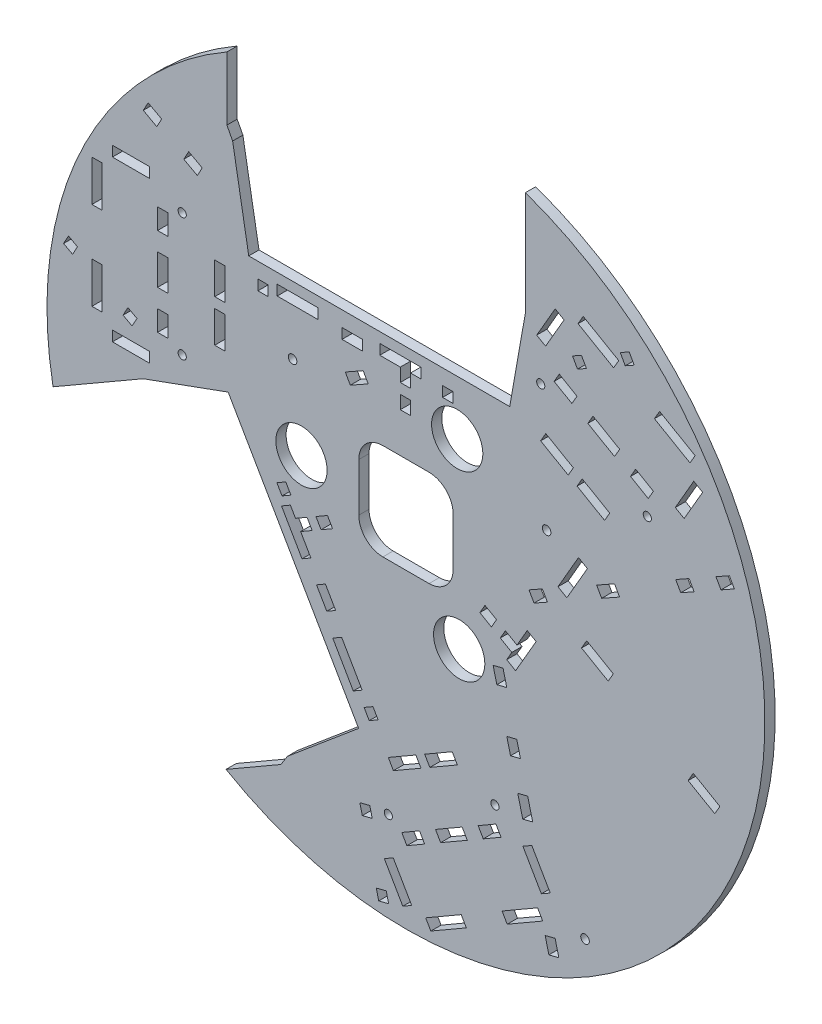
SolidWorks part; units mm, degrees
material "Balsa"
ref_plane "Plan de face" through (0, 0, 0) normal (0, 0, 1) x (1, 0, 0)
ref_plane "Plan de dessus" through (0, 0, 0) normal (0, 1, 0) x (1, 0, 0)
ref_plane "Plan de droite" through (0, 0, 0) normal (1, 0, 0) x (0, 0, -1)
sketch "Esquisse1" plane through (0, 0, 0) normal (0, 0, 1) x (1, 0, 0)
  circle A0 centre (148.0804, -12.1102) radius 175
  dimension "D1" = 350
extrude "Boss.-Extru.1" add sketch "Esquisse1" along normal blind 5
sketch "Esquisse2" plane through (0, 0, 5) normal (0, 0, 1) x (1, 0, 0)
  line L0 (135.3118, 53.7774) -> (135.3118, 48.7774)
  line L1 (5, 72.2774) -> (23, 72.2774)
  line L2 (5, 72.2774) -> (5, 67.2774)
  line L3 (5, 67.2774) -> (23, 67.2774)
  line L4 (23, 72.2774) -> (23, 67.2774)
  line L5 (-5, 62.2774) -> (0, 62.2774)
  line L6 (-5, 62.2774) -> (-5, 42.2774)
  line L7 (-5, 42.2774) -> (0, 42.2774)
  line L8 (0, 62.2774) -> (0, 42.2774)
  line L9 (-5, 19.2774) -> (0, 19.2774)
  line L10 (-5, 19.2774) -> (-5, -0.7226)
  line L11 (-5, -0.7226) -> (0, -0.7226)
  line L12 (0, 19.2774) -> (0, -0.7226)
  line L13 (5, -5.7226) -> (23, -5.7226)
  line L14 (5, -5.7226) -> (5, -10.7226)
  line L15 (5, -10.7226) -> (23, -10.7226)
  line L16 (23, -5.7226) -> (23, -10.7226)
  line L17 (27, 14.2774) -> (32, 14.2774)
  line L18 (27, 14.2774) -> (27, 4.2774)
  line L19 (27, 4.2774) -> (32, 4.2774)
  line L20 (32, 14.2774) -> (32, 4.2774)
  line L21 (27, 38.2774) -> (32, 38.2774)
  line L22 (27, 38.2774) -> (27, 23.2774)
  line L23 (27, 23.2774) -> (32, 23.2774)
  line L24 (32, 38.2774) -> (32, 23.2774)
  line L25 (27, 57.2774) -> (32, 57.2774)
  line L26 (27, 57.2774) -> (27, 47.2774)
  line L27 (27, 47.2774) -> (32, 47.2774)
  line L28 (32, 57.2774) -> (32, 47.2774)
  line L29 (54.86, 48.7774) -> (59.86, 48.7774)
  line L30 (54.86, 48.7774) -> (54.86, 33.2774)
  line L31 (54.86, 33.2774) -> (59.86, 33.2774)
  line L32 (59.86, 48.7774) -> (59.86, 33.2774)
  line L33 (54.86, 28.2774) -> (59.86, 28.2774)
  line L34 (54.86, 28.2774) -> (54.86, 12.7774)
  line L35 (54.86, 12.7774) -> (59.86, 12.7774)
  line L36 (59.86, 28.2774) -> (59.86, 12.7774)
  line L37 (85.3118, 53.7774) -> (105.3118, 53.7774)
  line L38 (85.3118, 53.7774) -> (85.3118, 48.7774)
  line L39 (85.3118, 48.7774) -> (105.3118, 48.7774)
  line L40 (105.3118, 53.7774) -> (105.3118, 48.7774)
  line L41 (145.3118, 37.2774) -> (150.3118, 37.2774)
  line L42 (145.3118, 37.2774) -> (145.3118, 30.7774)
  line L43 (145.3118, 30.7774) -> (150.3118, 30.7774)
  line L44 (150.3118, 37.2774) -> (150.3118, 30.7774)
  line L45 (135.3118, 48.7774) -> (145.3118, 48.7774)
  line L46 (155.3118, 48.7774) -> (135.3118, 48.7774) construction
  line L47 (145.3118, 48.7774) -> (145.3118, 42.2774)
  line L48 (145.3118, 42.2774) -> (150.3118, 42.2774)
  line L49 (150.3118, 42.2774) -> (150.3118, 48.7774)
  line L50 (150.3118, 48.7774) -> (155.3118, 48.7774)
  line L51 (155.3118, 48.7774) -> (155.3118, 53.7774)
  line L52 (155.3118, 53.7774) -> (135.3118, 53.7774)
  line L53 (292.7025, 69.6073) -> (283.7025, 54.0188)
  line L54 (292.7025, 69.6073) -> (288.3723, 72.1073)
  line L55 (288.3723, 72.1073) -> (279.3723, 56.5188)
  line L56 (283.7025, 54.0188) -> (279.3723, 56.5188)
  line L57 (289.0422, 83.2676) -> (286.5422, 78.9374)
  line L58 (289.0422, 83.2676) -> (271.7217, 93.2676)
  line L59 (271.7217, 93.2676) -> (269.2217, 88.9374)
  line L60 (286.5422, 78.9374) -> (269.2217, 88.9374)
  line L61 (251.8031, 104.7676) -> (249.3031, 100.4374)
  line L62 (251.8031, 104.7676) -> (234.4826, 114.7676)
  line L63 (234.4826, 114.7676) -> (231.9826, 110.4374)
  line L64 (249.3031, 100.4374) -> (231.9826, 110.4374)
  line L65 (225.1525, 108.6073) -> (216.1525, 93.0188)
  line L66 (225.1525, 108.6073) -> (220.8223, 111.1073)
  line L67 (220.8223, 111.1073) -> (211.8223, 95.5188)
  line L68 (216.1525, 93.0188) -> (211.8223, 95.5188)
  line L69 (231.473, 79.5547) -> (228.973, 75.2246)
  line L70 (231.473, 79.5547) -> (222.8127, 84.5547)
  line L71 (222.8127, 84.5547) -> (220.3127, 80.2246)
  line L72 (228.973, 75.2246) -> (220.3127, 80.2246)
  line L73 (252.2576, 67.5547) -> (249.7576, 63.2246)
  line L74 (252.2576, 67.5547) -> (239.2672, 75.0547)
  line L75 (239.2672, 75.0547) -> (236.7672, 70.7246)
  line L76 (249.7576, 63.2246) -> (236.7672, 70.7246)
  line L77 (268.7121, 58.0547) -> (266.2121, 53.7246)
  line L78 (268.7121, 58.0547) -> (260.0518, 63.0547)
  line L79 (260.0518, 63.0547) -> (257.5518, 58.7246)
  line L80 (266.2121, 53.7246) -> (257.5518, 58.7246)
  line L81 (247.4209, 38.1773) -> (244.9209, 33.8472)
  line L82 (247.4209, 38.1773) -> (233.9975, 45.9273)
  line L83 (233.9975, 45.9273) -> (231.4975, 41.5972)
  line L84 (244.9209, 33.8472) -> (231.4975, 41.5972)
  line L85 (229.6673, 48.4273) -> (227.1673, 44.0972)
  line L86 (229.6673, 48.4273) -> (216.2439, 56.1773)
  line L87 (216.2439, 56.1773) -> (213.7439, 51.8472)
  line L88 (227.1673, 44.0972) -> (213.7439, 51.8472)
  line L89 (211.5251, -33.996) -> (207.195, -31.496)
  line L90 (236.5251, 9.3053) -> (226.5251, -8.0153)
  line L91 (236.5251, 9.3053) -> (232.195, 11.8053)
  line L92 (232.195, 11.8053) -> (222.195, -5.5153)
  line L93 (226.5251, -8.0153) -> (222.195, -5.5153)
  line L94 (192.2357, -34.4063) -> (189.7357, -38.7364)
  line L95 (192.2357, -34.4063) -> (186.6065, -31.1563)
  line L96 (186.6065, -31.1563) -> (184.1065, -35.4864)
  line L97 (189.7357, -38.7364) -> (184.1065, -35.4864)
  line L98 (207.195, -31.496) -> (202.195, -40.1563)
  line L99 (202.195, -40.1563) -> (196.5658, -36.9063)
  line L100 (196.5658, -36.9063) -> (194.0658, -41.2364)
  line L101 (194.0658, -41.2364) -> (199.695, -44.4864)
  line L102 (199.695, -44.4864) -> (197.195, -48.8165)
  line L103 (197.195, -48.8165) -> (201.5251, -51.3165)
  line L104 (201.5251, -51.3165) -> (211.5251, -33.996)
  line L105 (146.5388, -178.2153) -> (137.5388, -162.6268)
  line L106 (146.5388, -178.2153) -> (150.869, -175.7153)
  line L107 (150.869, -175.7153) -> (141.869, -160.1268)
  line L108 (137.5388, -162.6268) -> (141.869, -160.1268)
  line L109 (160.1991, -181.8755) -> (157.6991, -177.5454)
  line L110 (160.1991, -181.8755) -> (177.5196, -171.8755)
  line L111 (177.5196, -171.8755) -> (175.0196, -167.5454)
  line L112 (157.6991, -177.5454) -> (175.0196, -167.5454)
  line L113 (197.4382, -160.3755) -> (194.9382, -156.0454)
  line L114 (197.4382, -160.3755) -> (214.7587, -150.3755)
  line L115 (214.7587, -150.3755) -> (212.2587, -146.0454)
  line L116 (194.9382, -156.0454) -> (212.2587, -146.0454)
  line L117 (214.0888, -139.2153) -> (205.0888, -123.6268)
  line L118 (214.0888, -139.2153) -> (218.4189, -136.7153)
  line L119 (218.4189, -136.7153) -> (209.4189, -121.1268)
  line L120 (205.0888, -123.6268) -> (209.4189, -121.1268)
  line L121 (185.7683, -130.1627) -> (183.2683, -125.8326)
  line L122 (185.7683, -130.1627) -> (194.4286, -125.1627)
  line L123 (194.4286, -125.1627) -> (191.9286, -120.8326)
  line L124 (183.2683, -125.8326) -> (191.9286, -120.8326)
  line L125 (164.9837, -142.1627) -> (162.4837, -137.8326)
  line L126 (164.9837, -142.1627) -> (177.9741, -134.6627)
  line L127 (177.9741, -134.6627) -> (175.4741, -130.3326)
  line L128 (162.4837, -137.8326) -> (175.4741, -130.3326)
  line L129 (148.5292, -151.6627) -> (146.0292, -147.3326)
  line L130 (148.5292, -151.6627) -> (157.1895, -146.6627)
  line L131 (157.1895, -146.6627) -> (154.6895, -142.3326)
  line L132 (146.0292, -147.3326) -> (154.6895, -142.3326)
  line L133 (141.9604, -123.2852) -> (139.4604, -118.9551)
  line L134 (141.9604, -123.2852) -> (155.3838, -115.5352)
  line L135 (155.3838, -115.5352) -> (152.8838, -111.2051)
  line L136 (139.4604, -118.9551) -> (152.8838, -111.2051)
  line L137 (159.7139, -113.0352) -> (157.2139, -108.7051)
  line L138 (159.7139, -113.0352) -> (173.1373, -105.2852)
  line L139 (173.1373, -105.2852) -> (170.6373, -100.9551)
  line L140 (157.2139, -108.7051) -> (170.6373, -100.9551)
  line L141 (97.4044, -56.1119) -> (101.7345, -53.6119)
  line L142 (122.4044, -99.4132) -> (112.4044, -82.0927)
  line L143 (122.4044, -99.4132) -> (126.7345, -96.9132)
  line L144 (126.7345, -96.9132) -> (116.7345, -79.5927)
  line L145 (112.4044, -82.0927) -> (116.7345, -79.5927)
  line L146 (106.6938, -39.2017) -> (104.1938, -34.8716)
  line L147 (106.6938, -39.2017) -> (112.323, -35.9517)
  line L148 (112.323, -35.9517) -> (109.823, -31.6216)
  line L149 (104.1938, -34.8716) -> (109.823, -31.6216)
  line L150 (101.7345, -53.6119) -> (96.7345, -44.9517)
  line L151 (96.7345, -44.9517) -> (102.3637, -41.7017)
  line L152 (102.3637, -41.7017) -> (99.8637, -37.3716)
  line L153 (99.8637, -37.3716) -> (94.2345, -40.6216)
  line L154 (94.2345, -40.6216) -> (91.7345, -36.2914)
  line L155 (91.7345, -36.2914) -> (87.4044, -38.7914)
  line L156 (87.4044, -38.7914) -> (97.4044, -56.1119)
  line L157 (135.3118, 53.7774) -> (135.3118, 48.7774) construction
  line L158 (105.3118, 53.7774) -> (135.3118, 53.7774) construction
  point P83 (148.0804, -12.1102)
  point P192 (148.0804, -12.1102)
  point P193 (148.0804, -12.1102)
  dimension "D1" = 3
extrude "Enlèv. mat.-Extru.1" cut sketch "Esquisse2" against normal blind 5
sketch "Esquisse6" plane through (0, 0, 5) normal (0, 0, 1) x (1, 0, 0)
  line L0 (93.9998, -7.2151) -> (100.2998, -18.127) construction
  line L1 (206.3213, 102.2219) -> (206.3213, 185.5637)
  line L2 (125.0804, -35.6102) -> (171.0804, -35.6102) construction
  line L3 (125.0804, -35.6102) -> (125.0804, 11.3898) construction
  line L4 (125.0804, 11.3898) -> (171.0804, 11.3898) construction
  line L5 (171.0804, -35.6102) -> (171.0804, 11.3898) construction
  line L6 (125.0804, -35.6102) -> (171.0804, 11.3898) construction
  line L7 (125.0804, 11.3898) -> (171.0804, -35.6102) construction
  line L8 (206.3213, 185.5637) -> (60.7972, 185.5637)
  line L9 (71.4438, 58.7774) -> (63.5848, 103.3483)
  line L10 (71.4438, 58.7774) -> (198.6608, 58.7774)
  line L11 (198.6608, 58.7774) -> (206.3213, 102.2219)
  line L12 (60.7972, 185.5637) -> (60.7972, 108.6824)
  line L13 (19.9456, -18.8381) -> (-52.2306, -60.5091)
  line L14 (-52.2306, -60.5091) -> (20.5314, -186.5366)
  line L15 (63.5848, 103.3483) -> (60.7972, 108.6824)
  line L16 (125.0083, -113.9232) -> (90.3383, -143.0148)
  line L17 (125.0083, -113.9232) -> (61.3998, -3.7501)
  line L18 (61.3998, -3.7501) -> (19.9456, -18.8381)
  line L19 (136.8304, -23.8602) -> (159.3304, -23.8602) construction
  line L20 (236.1714, -21.3074) -> (249.1617, -28.8074)
  line L21 (236.1714, -21.3074) -> (233.6714, -25.6375)
  line L22 (249.1617, -28.8074) -> (246.6617, -33.1375)
  line L23 (233.6714, -25.6375) -> (246.6617, -33.1375)
  line L24 (288.1329, -51.3074) -> (301.1233, -58.8074)
  line L25 (288.1329, -51.3074) -> (285.6329, -55.6375)
  line L26 (301.1233, -58.8074) -> (298.6233, -63.1375)
  line L27 (285.6329, -55.6375) -> (298.6233, -63.1375)
  line L28 (226.5251, -8.0153) -> (236.5251, 9.3053) construction
  line L29 (279.3723, 56.5188) -> (283.7025, 54.0188) construction
  line L30 (136.8304, -0.3602) -> (159.3304, -0.3602) construction
  line L31 (64.5427, 103.6743) -> (63.0102, 106.6067) construction
  line L32 (20.5314, -186.5366) -> (87.1126, -148.0959)
  line L33 (90.3383, -143.0148) -> (87.1126, -148.0959)
  line L34 (125.0804, -23.8602) -> (125.0804, -0.3602)
  line L35 (136.8304, -35.6102) -> (159.3304, -35.6102)
  line L36 (159.3304, -35.6102) -> (159.6478, -35.9264)
  line L37 (171.0804, -23.8602) -> (171.0804, -0.3602)
  line L38 (159.3304, 11.3898) -> (136.8304, 11.3898)
  circle A0 centre (173.06, 32.2774) radius 12.5
  circle A1 centre (174.0314, -55.9369) radius 12.5
  circle A2 centre (97.1498, -12.671) radius 12.5
  arc A3 (125.0804, -23.8602) -> (136.8304, -35.6102) centre (136.8304, -23.8602) ccw
  arc A4 (171.0804, -23.8602) -> (159.3304, -35.6102) centre (159.3304, -23.8602) cw
  arc A5 (171.0804, -0.3602) -> (159.3304, 11.3898) centre (159.3304, -0.3602) ccw
  arc A6 (125.0804, -0.3602) -> (136.8304, 11.3898) centre (136.8304, -0.3602) cw
  point P2 (148.0804, -12.1102)
  point P8 (148.0804, -12.1102)
  point P10 (148.0804, -12.1102)
  point P35 (148.0804, -12.1102)
  point P48 (148.0804, -12.1102)
  dimension "D12" = 25
  dimension "D23" = 11.75
  dimension "D3" = 47
  dimension "D4" = 46
  dimension "D5" = 70.8876
  dimension "D6" = 50.5804
  dimension "D7" = 127.217
  dimension "D8" = 100
  dimension "D9" = 100
  dimension "D10" = 145.5241
  dimension "D11" = 43.4444
  dimension "D13" = 5
  dimension "D14" = 15
  dimension "D15" = 15
  dimension "D16" = 45
  dimension "D17" = 15
  dimension "D18" = 89
  dimension "D19" = 2
  dimension "D20" = 1
  dimension "D21" = 11.75
  dimension "D22" = 11.75
  dimension "D1" = 3
extrude "Enlèv. mat.-Extru.6" cut sketch "Esquisse6" against normal blind 5 contours L33 L16 L17 L18 L13 L14 L32 | A2 | L15 L9 L10 L11 L1 L8 L12 | A6 L34 A3 L35 A4 L37 A5 L38 | A1 | A0 | L25 L27 L26 L24 | L21 L23 L22 L20
hole_wizard "Trous de centrage Ø4.0mm1" positions "Esquisse7" profile "Esquisse8" hole size "Ø4.0" standard "Ansi Metric" end condition through all
sketch "Esquisse7" plane through (148.0804, -12.1102, -78) normal (0, 0, -1) x (1, 0, 0)
  point P0 (65.7012, -88.0226)
  point P3 (117.6627, -58.0226)
  point P6 (-109.0804, -72.8876)
  point P9 (-109.0804, -12.8876)
  point P12 (-8.5823, 130.9102)
  point P15 (43.3792, 100.9102)
sketch "Esquisse8" plane through (213.7816, 75.9124, -78) normal (1, 0, 0) x (0, 1, 0)
  line L0 (0, 0) -> (0, 83)
  line L1 (0, 83) -> (2, 83)
  line L2 (2, 83) -> (2, 0)
  line L3 (2, 0) -> (0, 0)
  line L4 (0, -6.35) -> (0, 107.95) construction
  dimension "Diamètre du perçage jusqu'au prochain" = 4
  dimension "Profondeur du perçage jusqu'au prochain" = 83
sketch "Esquisse9" plane through (0, 0, 5) normal (0, 0, 1) x (1, 0, 0)
  line L0 (301.6473, 32.8747) -> (299.2005, 37.2351)
  line L1 (301.6473, 32.8747) -> (308.1879, 36.5449)
  line L2 (299.2005, 37.2351) -> (305.7411, 40.9053)
  line L3 (308.1879, 36.5449) -> (305.7411, 40.9053)
  line L4 (282.0254, 21.8642) -> (279.5786, 26.2246)
  line L5 (282.0254, 21.8642) -> (288.566, 25.5344)
  line L6 (279.5786, 26.2246) -> (286.1192, 29.8948)
  line L7 (288.566, 25.5344) -> (286.1192, 29.8948)
  line L8 (252.2089, 5.133) -> (249.7621, 9.4935)
  line L9 (252.2089, 5.133) -> (243.488, 0.2395)
  line L10 (249.7621, 9.4935) -> (241.0412, 4.5999)
  line L11 (243.488, 0.2395) -> (241.0412, 4.5999)
  line L12 (214.6084, -10.2326) -> (217.0552, -14.593)
  line L13 (214.6084, -10.2326) -> (208.0678, -13.9027)
  line L14 (217.0552, -14.593) -> (210.5146, -18.2632)
  line L15 (208.0678, -13.9027) -> (210.5146, -18.2632)
  line L16 (217.0552, -14.593) -> (243.488, 0.2395) construction
  line L17 (214.6084, -10.2326) -> (217.0552, -14.593) construction
  line L18 (259.3473, 106.6065) -> (254.9869, 104.1597)
  line L19 (259.3473, 106.6065) -> (256.9005, 110.9669)
  line L20 (254.9869, 104.1597) -> (252.5401, 108.5201)
  line L21 (256.9005, 110.9669) -> (252.5401, 108.5201)
  line L22 (236.0696, 93.5445) -> (231.7091, 91.0977)
  line L23 (236.0696, 93.5445) -> (233.6228, 97.9049)
  line L24 (231.7091, 91.0977) -> (229.2624, 95.4581)
  line L25 (233.6228, 97.9049) -> (229.2624, 95.4581)
  line L26 (129.6754, 33.8428) -> (120.9546, 28.9492)
  line L27 (129.6754, 33.8428) -> (127.2286, 38.2032)
  line L28 (120.9546, 28.9492) -> (118.5078, 33.3096)
  line L29 (127.2286, 38.2032) -> (118.5078, 33.3096)
  line L30 (259.3473, 106.6065) -> (120.9546, 28.9492) construction
  line L31 (301.6473, 32.8747) -> (217.0552, -14.593) construction
  line L32 (-16.4384, 23.2791) -> (-12.0459, 20.8904)
  line L33 (-16.4384, 23.2791) -> (-18.8272, 18.8866)
  line L34 (-12.0459, 20.8904) -> (-14.4347, 16.4979)
  line L35 (-18.8272, 18.8866) -> (-14.4347, 16.4979)
  line L36 (12.552, 7.5136) -> (16.9445, 5.1249)
  line L37 (12.552, 7.5136) -> (10.1633, 3.1211)
  line L38 (16.9445, 5.1249) -> (14.5558, 0.7324)
  line L39 (10.1633, 3.1211) -> (14.5558, 0.7324)
  line L42 (-26.9196, -12.1102) -> (148.0804, -12.1102) construction
  line L44 (22.4127, 98.9071) -> (29.0015, 95.324)
  line L45 (22.4127, 98.9071) -> (20.024, 94.5146)
  line L46 (29.0015, 95.324) -> (26.6128, 90.9315)
  line L47 (20.024, 94.5146) -> (26.6128, 90.9315)
  line L48 (42.179, 88.1579) -> (48.7677, 84.5748)
  line L49 (42.179, 88.1579) -> (39.7903, 83.7654)
  line L50 (48.7677, 84.5748) -> (46.379, 80.1823)
  line L51 (39.7903, 83.7654) -> (46.379, 80.1823)
  line L53 (148.0804, -12.1102) -> (9.6568, -109.2191) construction
  line L55 (129.7636, 187.6323) -> (148.0804, -12.1102) construction
  circle A0 centre (148.0804, -12.1102) radius 175 construction
  line B0 (154.106, -73.5915) -> (185.6214, -199.5155) construction
  line B1 (126.7996, -149.8343) -> (125.5857, -144.9839)
  line B2 (130.4361, -143.77) -> (125.5857, -144.9839)
  line B3 (131.65, -148.6204) -> (126.7996, -149.8343)
  line B4 (131.65, -148.6204) -> (130.4361, -143.77)
  line B5 (134.8115, -181.8469) -> (133.5976, -176.9965)
  line B6 (138.448, -175.7826) -> (133.5976, -176.9965)
  line B7 (139.6619, -180.633) -> (134.8115, -181.8469)
  line B8 (139.6619, -180.633) -> (138.448, -175.7826)
  line B9 (190.562, -54.5014) -> (195.4124, -53.2875)
  line B10 (197.2333, -60.5631) -> (195.4124, -53.2875)
  line B11 (192.3829, -61.777) -> (190.562, -54.5014)
  line B12 (192.3829, -61.777) -> (197.2333, -60.5631)
  line B13 (202.089, -79.9647) -> (197.2386, -81.1786)
  line B14 (199.0595, -88.4542) -> (197.2386, -81.1786)
  line B15 (203.9099, -87.2403) -> (202.089, -79.9647)
  line B16 (203.9099, -87.2403) -> (199.0595, -88.4542)
  line B17 (222.6043, -161.9364) -> (217.7539, -163.1503)
  line B18 (215.933, -155.8747) -> (217.7539, -163.1503)
  line B19 (220.7834, -154.6608) -> (222.6043, -161.9364)
  line B20 (220.7834, -154.6608) -> (215.933, -155.8747)
  dimension "D9" = 170.2546
  dimension "D1" = 10
  dimension "D2" = 5
  dimension "D3" = 7.5
  dimension "D4" = 10
  dimension "D5" = 7.5
  dimension "D6" = 7.5
  dimension "D7" = 5
  dimension "D8" = 117
  dimension "D10" = 167.3371
  dimension "D11" = 69
  dimension "D12" = 35.051
  dimension "D13" = 30.31
  dimension "D14" = 5
sketch_block_instance "Bloc1-1"
sketch_block "Bloc1"
extrude "Holes catchers of glass" cut sketch "Esquisse9" against normal blind 10
sketch "Esquisse10" plane through (0, 0, 5) normal (0, 0, 1) x (1, 0, 0)
  line L0 (89.4961, -27.6144) -> (91.9961, -31.9445)
  line L1 (89.4961, -27.6144) -> (85.1672, -30.1137)
  line L2 (91.9961, -31.9445) -> (87.6672, -34.4438)
  line L3 (85.1672, -30.1137) -> (87.6672, -34.4438)
  dimension "D1" = 4.9986
extrude "Holes boards servo" cut sketch "Esquisse10" against normal blind 10
sketch "Esquisse11" plane through (0, 0, 5) normal (0, 0, 1) x (1, 0, 0)
  line L0 (109.4829, -72.2325) -> (104.4829, -63.5722)
  line L1 (109.4829, -72.2325) -> (113.813, -69.7325)
  line L2 (104.4829, -63.5722) -> (108.813, -61.0722)
  line L3 (113.813, -69.7325) -> (108.813, -61.0722)
  line L4 (125.166, -99.3964) -> (108.8992, -71.2215) construction
  line L6 (116.7345, -79.5927) -> (112.4044, -82.0927) construction
  line L7 (130.166, -108.0567) -> (134.4961, -105.5567)
  line L8 (130.166, -108.0567) -> (127.666, -103.7266)
  line L9 (134.4961, -105.5567) -> (131.9961, -101.2266)
  line L10 (127.666, -103.7266) -> (131.9961, -101.2266)
  line L11 (207.4302, -101.3064) -> (209.8581, -111.0072)
  line L12 (170.9253, 51.2774) -> (165.9253, 51.2774)
  line L13 (170.9253, 51.2774) -> (170.9253, 46.2774)
  line L14 (170.9253, 46.2774) -> (165.9253, 46.2774)
  line L15 (165.9253, 51.2774) -> (165.9253, 46.2774)
  line L16 (126.9253, 51.2774) -> (116.9253, 51.2774)
  line L17 (126.9253, 51.2774) -> (126.9253, 46.2774)
  line L18 (126.9253, 46.2774) -> (116.9253, 46.2774)
  line L19 (116.9253, 51.2774) -> (116.9253, 46.2774)
  line L20 (80.9253, 51.2774) -> (75.9253, 51.2774)
  line L21 (80.9253, 51.2774) -> (80.9253, 46.2774)
  line L22 (80.9253, 46.2774) -> (75.9253, 46.2774)
  line L23 (75.9253, 51.2774) -> (75.9253, 46.2774)
  line L24 (207.4302, -101.3064) -> (202.5798, -102.5203)
  line L25 (209.8581, -111.0072) -> (205.0077, -112.2211)
  line L26 (202.5798, -102.5203) -> (205.0077, -112.2211)
  line L27 (203.9099, -87.2403) -> (202.089, -79.9647) construction
  line L28 (220.7834, -154.6608) -> (215.933, -155.8747) construction
  dimension "D1" = 10
  dimension "D2" = 10
  dimension "D3" = 5
  dimension "D4" = 5
  dimension "D5" = 5
  dimension "D6" = 10
  dimension "D7" = 45
extrude "Enlèv. mat.-Extru.7" cut sketch "Esquisse11" against normal blind 5
hole_wizard "Trou taraudé M51" positions "Esquisse12" profile "Esquisse13" tap size "M5" standard "ISO" end condition through all
sketch "Esquisse12" plane through (148.0804, -12.1102, 262) normal (0, 0, 1) x (-1, 0, 0)
  point P0 (-68.569, -27.6625)
  point P2 (55.2809, -37.9834)
  point P4 (-87.2993, 135.5593)
sketch "Esquisse13" plane through (216.6494, 15.5524, 262) normal (1, 0, 0) x (0, -1, 0)
  line L0 (0, 0) -> (0, 262)
  line L1 (0, 262) -> (2.1, 262)
  line L2 (2.1, 262) -> (2.1, 0)
  line L3 (2.1, 0) -> (0, 0)
  line L4 (0, -6.35) -> (0, 107.95) construction
  dimension "Diamètre principal du filetage" = 4.2
  dimension "Profondeur du trou pour taraudage jusqu'au prochain" = 262
